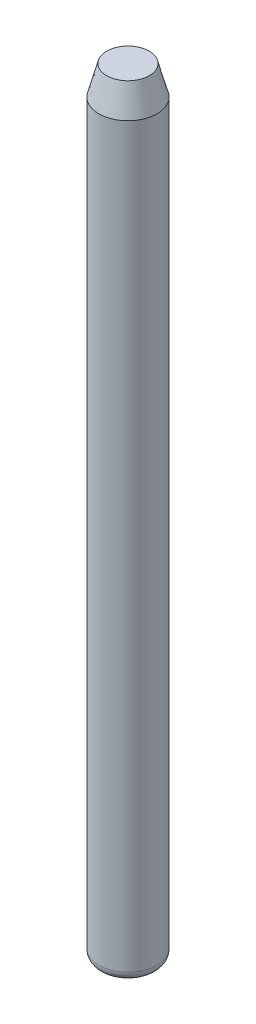
SolidWorks part; units mm, degrees
ref_plane "Front Plane" through (0, 0, 0) normal (0, 0, 1) x (1, 0, 0)
ref_plane "Top Plane" through (0, 0, 0) normal (0, 1, 0) x (1, 0, 0)
ref_plane "Right Plane" through (0, 0, 0) normal (1, 0, 0) x (0, 0, -1)
sketch "Sketch1" plane through (0, 0, 0) normal (0, 1, 0) x (1, 0, 0)
  circle A0 centre (0, 0) radius 1.5
  dimension "D1" = 3
extrude "Boss-Extrude1" add sketch "Sketch1" along normal blind 40
chamfer "Chamfer1" distance 1.5 angle 15 1 edges at (0, 40, 1.5)
fillet "Fillet1" radius 0.5 1 edges at (0, 0, 1.5)
